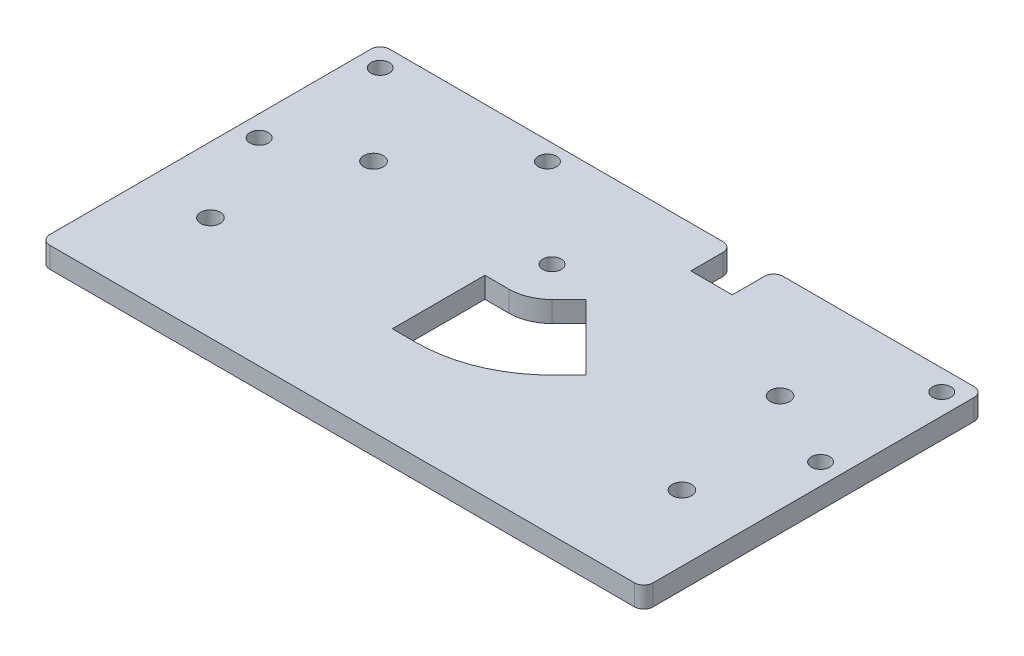
SolidWorks part; units mm, degrees
ref_plane "Front Plane" through (0, 0, 0) normal (0, 0, 1) x (1, 0, 0)
ref_plane "Top Plane" through (0, 0, 0) normal (0, 1, 0) x (1, 0, 0)
ref_plane "Right Plane" through (0, 0, 0) normal (1, 0, 0) x (0, 0, -1)
sketch "Sketch1" plane through (0, 0, 0) normal (0, 1, 0) x (1, 0, 0)
  line L0 (-65, 0) -> (65, 0) construction
  line L1 (63, 20.3) -> (21.8, 20.3)
  line L2 (65, 18.3) -> (65, -50.9)
  line L3 (63, -52.9) -> (-63, -52.9)
  line L4 (-65, 18.3) -> (-65, -50.9)
  line L5 (-65, -14.8) -> (65, -14.8) construction
  line L6 (-65, -46.169) -> (65, -46.169) construction
  line L7 (-50.8, -14.8) -> (-50.8, -46.169) construction
  line L8 (10.87, 18.3) -> (10.87, 11.37)
  line L9 (10.87, 11.37) -> (19.8, 11.37)
  line L10 (19.8, 18.3) -> (19.8, 11.37)
  line L11 (0, 20.3) -> (0, -52.9) construction
  line L12 (8.87, 20.3) -> (-63, 20.3)
  line L13 (-43.8023, -14.8) -> (-43.8023, 20.3) construction
  line L14 (-5.3283, -2.3397) -> (-43.8023, -2.3397) construction
  line L15 (-5.3283, -2.3397) -> (-10.5129, -2.3397) construction
  line L16 (-5.3283, -31.5897) -> (-10.5083, -31.5897)
  line L17 (-10.5114, -11.6297) -> (-10.5083, -31.5897)
  line L18 (-5.3283, -11.6297) -> (-10.5114, -11.6297)
  line L19 (-5.3283, -2.3397) -> (-5.3283, -18.7889) construction
  line L20 (-5.3283, -2.3397) -> (-1.6655, 1.3232) construction
  line L21 (-5.3283, -2.3397) -> (15.3545, -23.0225) construction
  line L23 (15.3545, -23.0225) -> (19.0174, -19.3597)
  line L24 (1.2407, -8.9087) -> (4.9035, -5.2459)
  line L25 (4.9035, -5.2459) -> (19.0174, -19.3597)
  circle A0 centre (-60.5, 15.8) radius 1.975
  circle A1 centre (60.5, 15.8) radius 1.975
  circle A2 centre (60.5, -10.3) radius 1.975
  circle A3 centre (-60.5, -10.3) radius 1.975
  circle A4 centre (-25.0043, 16.35) radius 1.975
  arc A5 (10.87, 18.3) -> (8.87, 20.3) centre (8.87, 18.3) ccw
  circle A6 centre (-5.3283, -2.3397) radius 1.975
  arc A7 (63, 20.3) -> (65, 18.3) centre (63, 18.3) cw
  arc A8 (21.8, 20.3) -> (19.8, 18.3) centre (21.8, 18.3) ccw
  arc A9 (-63, 20.3) -> (-65, 18.3) centre (-63, 18.3) ccw
  arc A10 (65, -50.9) -> (63, -52.9) centre (63, -50.9) cw
  arc A11 (-63, -52.9) -> (-65, -50.9) centre (-63, -50.9) cw
  circle A12 centre (-50.8, -30.4845) radius 2.1082
  circle A13 centre (50.8, -30.4845) radius 2.1082
  circle A14 centre (-43.8023, -2.3397) radius 2.1082
  circle A15 centre (43.8023, -2.3397) radius 2.1082
  arc A16 (-5.3283, -31.5897) -> (15.3545, -23.0225) centre (-5.3283, -2.3397) ccw
  arc A17 (-5.3283, -11.6297) -> (1.2407, -8.9087) centre (-5.3283, -2.3397) ccw
  point P0 (0, 0)
  point P26 (10.87, 20.3)
  point P31 (65, 20.3)
  point P36 (-65, 20.3)
  point P61 (0, 0)
  dimension "D6" = 3.95
  dimension "D9" = 3.95
  dimension "D12" = 2
  dimension "D13" = 3.95
  dimension "D16" = 3.95
  dimension "D20" = 2
  dimension "D21" = 2
  dimension "D24" = 4.2164
  dimension "D27" = 4.2164
  dimension "D29" = 58.5
  dimension "D32" = 18.58
  dimension "D1" = 130
  dimension "D2" = 30.6
  dimension "D3" = 8.93
  dimension "D4" = 8.93
  dimension "D5" = 45.2
  dimension "D7" = 4.5
  dimension "D8" = 4.5
  dimension "D10" = 35.5
  dimension "D11" = 3.95
  dimension "D14" = 73.2
  dimension "D15" = 4.5
  dimension "D17" = 4.6793
  dimension "D18" = 5.3283
  dimension "D19" = 20.3
  dimension "D22" = 38.1
  dimension "D23" = 31.369
  dimension "D25" = 50.8
  dimension "D26" = 43.8023
  dimension "D28" = 38.474
  dimension "D30" = 5.1845
  dimension "D31" = 5.18
  dimension "D33" = 45
  dimension "D34" = 90
  dimension "D35" = 5.18
  dimension "D36" = 5.18
  dimension "D37" = 5.1831
  dimension "D38" = 5.18
extrude "Boss-Extrude1" add sketch "Sketch1" along normal blind 4.5
